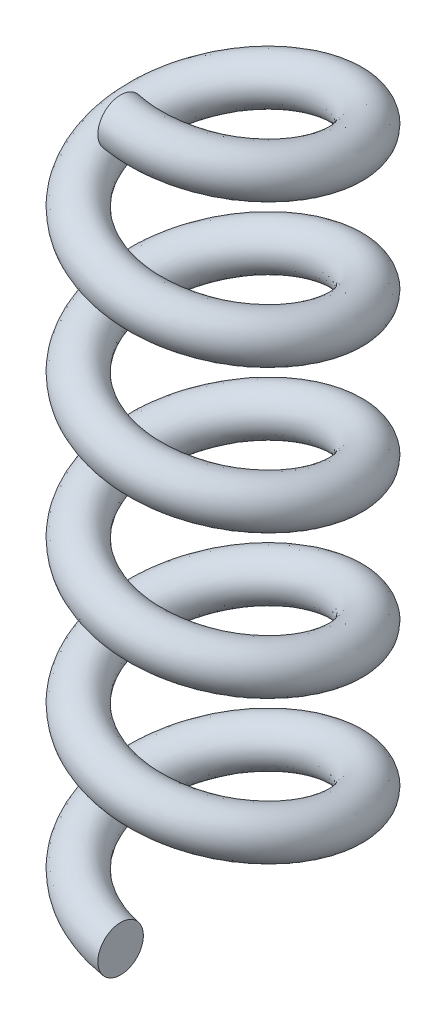
SolidWorks part; units mm, degrees
ref_plane "前视基准面" through (0, 0, 0) normal (0, 0, 1) x (1, 0, 0)
ref_plane "上视基准面" through (0, 0, 0) normal (0, 1, 0) x (1, 0, 0)
ref_plane "右视基准面" through (0, 0, 0) normal (1, 0, 0) x (0, 0, -1)
sketch "草图1" plane through (0, 0, 0) normal (0, 1, 0) x (1, 0, 0)
  circle A0 centre (0, 0) radius 4.5
  dimension "D1" = 9
curve "螺旋线/涡状线1" pitch 6.3 height 31.5 turns 5
sketch "草图2" plane through (0, 0, 0) normal (1, 0, 0) x (0, 0, -1)
  circle A0 centre (-4.5, 0) radius 1
  spline S0 degree 3 poles (-4.5, 0) (-4.5, 0.1304) (-4.2657, 0.3941) (-3.2648, 0.7874) (-1.7669, 1.1813) (0, 1.575) (1.7669, 1.9688) (3.2648, 2.3625) (4.2657, 2.7563) (4.6172, 3.15) (4.2657, 3.5438) (3.2648, 3.9375) (1.2676, 4.4625) (-1.2676, 4.9875) (-3.2648, 5.5125) (-4.2657, 5.9063) (-4.6172, 6.3) (-4.2657, 6.6938) (-3.2648, 7.0875) (-1.2676, 7.6125) (1.2676, 8.1375) (3.2648, 8.6625) (4.2657, 9.0563) (4.6172, 9.45) (4.2657, 9.8437) (3.2648, 10.2375) (1.2676, 10.7625) (-1.2676, 11.2875) (-3.2648, 11.8125) (-4.2657, 12.2063) (-4.6172, 12.6) (-4.2657, 12.9938) (-3.2648, 13.3875) (-1.2676, 13.9125) (1.2676, 14.4375) (3.2648, 14.9625) (4.2657, 15.3563) (4.6172, 15.75) (4.2657, 16.1437) (3.2648, 16.5375) (1.2676, 17.0625) (-1.2676, 17.5875) (-3.2648, 18.1125) (-4.2657, 18.5062) (-4.6172, 18.9) (-4.2657, 19.2937) (-3.2648, 19.6875) (-1.2676, 20.2125) (1.2676, 20.7375) (3.2648, 21.2625) (4.2657, 21.6562) (4.6172, 22.05) (4.2657, 22.4437) (3.2648, 22.8375) (1.2676, 23.3625) (-1.2676, 23.8875) (-3.2648, 24.4125) (-4.2657, 24.8062) (-4.6172, 25.2) (-4.2657, 25.5937) (-3.2648, 25.9875) (-1.2676, 26.5125) (1.2676, 27.0375) (3.2648, 27.5625) (4.2657, 27.9562) (4.6172, 28.35) (4.2657, 28.7437) (3.2648, 29.1375) (1.7669, 29.5312) (0, 29.925) (-1.7669, 30.3187) (-3.2648, 30.7126) (-4.2657, 31.1059) (-4.5, 31.3696) (-4.5, 31.5) knots 0 0 0 0 0.0125 0.025 0.0375 0.05 0.0625 0.075 0.0875 0.1 0.1125 0.125 0.1375 0.1625 0.175 0.1875 0.2 0.2125 0.225 0.2375 0.2625 0.275 0.2875 0.3 0.3125 0.325 0.3375 0.3625 0.375 0.3875 0.4 0.4125 0.425 0.4375 0.4625 0.475 0.4875 0.5 0.5125 0.525 0.5375 0.5625 0.575 0.5875 0.6 0.6125 0.625 0.6375 0.6625 0.675 0.6875 0.7 0.7125 0.725 0.7375 0.7625 0.775 0.7875 0.8 0.8125 0.825 0.8375 0.8625 0.875 0.8875 0.9 0.9125 0.925 0.9375 0.95 0.9625 0.975 0.9875 1 1 1 1 construction
  dimension "D1" = 2
sweep "扫描1" add profiles "草图2" path "螺旋线/涡状线1"
sketch "草图3" plane through (0, 0, 0) normal (0, 1, 0) x (1, 0, 0)
  circle A0 centre (0, 0) radius 12.444 construction
